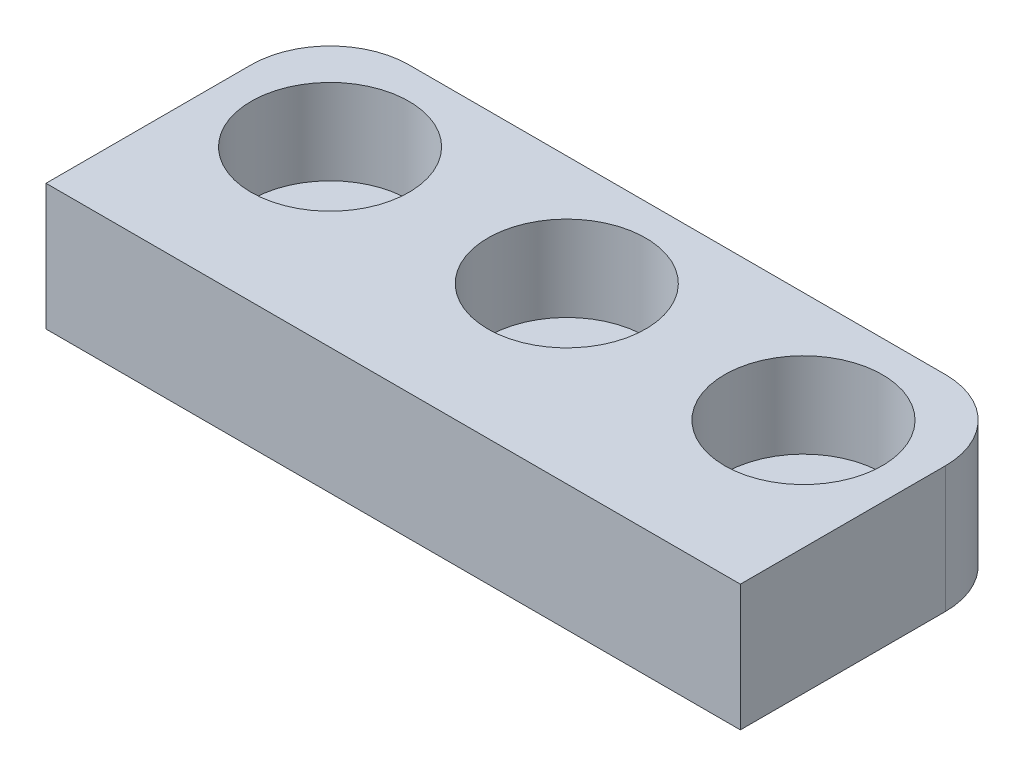
SolidWorks part; units mm, degrees
material "K110"
ref_plane "Front Plane" through (0, 0, 0) normal (0, 0, 1) x (1, 0, 0)
ref_plane "Top Plane" through (0, 0, 0) normal (0, 1, 0) x (1, 0, 0)
ref_plane "Right Plane" through (0, 0, 0) normal (1, 0, 0) x (0, 0, -1)
sketch "Sketch1" plane through (0, 0, 0) normal (0, 1, 0) x (1, 0, 0)
  line L1 (-22, -9) -> (22, -9)
  line L2 (-22, -9) -> (-22, 9)
  line L3 (-22, 9) -> (22, 9)
  line L4 (22, -9) -> (22, 9)
  line L5 (-22, -9) -> (22, 9) construction
  line L6 (-22, 9) -> (22, -9) construction
  point P0 (0, 0)
  dimension "D1" = 44
  dimension "D2" = 18
extrude "Boss-Extrude1" add sketch "Sketch1" against normal blind 8
hole_wizard "CBORE for M5 Hex Socket Head Cap Screw1" positions "Sketch5" profile "Sketch3" counterbore size "M5" standard "ISO" end condition through all
sketch "Sketch5" plane through (0, 0, 0) normal (0, 1, 0) x (1, 0, 0)
  line L0 (0, 9) -> (0, -9) construction
  line L1 (22, 9) -> (-22, 9) construction
  line L2 (-22, -9) -> (22, -9) construction
  point P0 (-15, 2)
  point P2 (0, 2)
  point P5 (15, 2)
  point P19 (0, 1.6302)
  dimension "D1" = 30
  dimension "D2" = 7
sketch "Sketch3" plane through (-15, 0, -2) normal (1, 0, 0) x (0, 0, 1)
  line L0 (0, 0) -> (0, 8)
  line L1 (0, 8) -> (2.65, 8)
  line L3 (2.65, 8) -> (2.65, 5.4)
  line L4 (2.65, 5.4) -> (5, 5.4)
  line L5 (5, 5.4) -> (5, 0)
  line L7 (5, 0) -> (0, 0)
  line L11 (0, -6.35) -> (0, 107.95) construction
  dimension "Thru Hole Dia." = 5.3
  dimension "Thru Hole Depth" = 8
  dimension "C'Bore Dia." = 10
  dimension "C'Bore Depth" = 5.4
fillet "Fillet1" radius 5 2 edges at (22, -4, -9) (-22, -4, -9)
